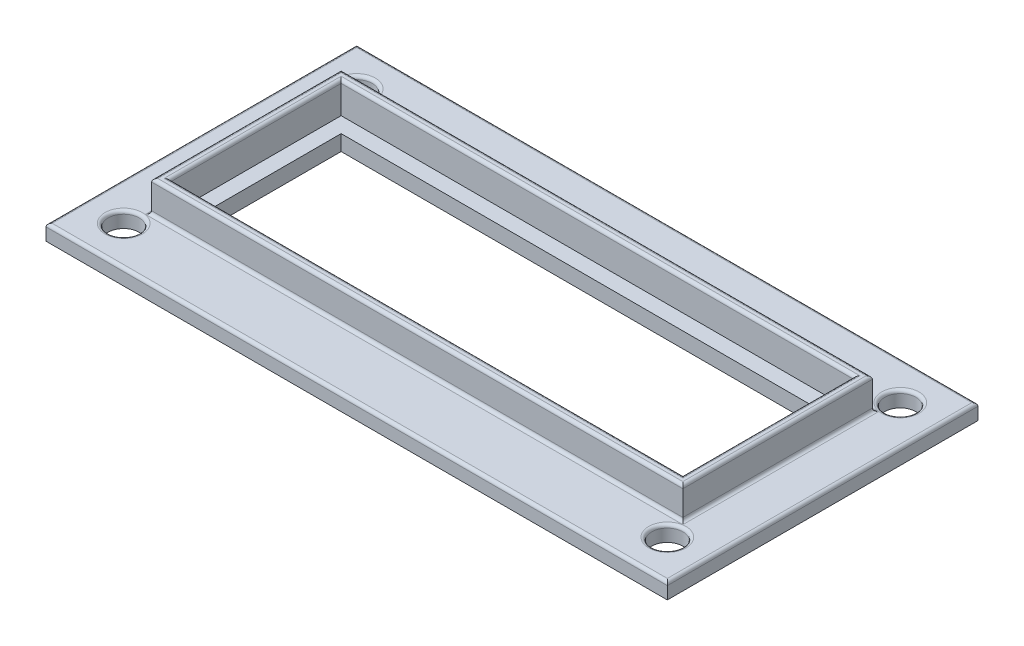
SolidWorks part; units mm, degrees
ref_plane "Front Plane" through (0, 0, 0) normal (0, 0, 1) x (1, 0, 0)
ref_plane "Top Plane" through (0, 0, 0) normal (0, 1, 0) x (1, 0, 0)
ref_plane "Right Plane" through (0, 0, 0) normal (1, 0, 0) x (0, 0, -1)
sketch "Sketch1" plane through (0, 0, 0) normal (0, 1, 0) x (1, 0, 0)
  line L0 (-85.5, 30.5) -> (-85.5, -30.5)
  line L1 (-82.5, 27.5) -> (82.5, 27.5)
  line L2 (-82.5, 27.5) -> (-82.5, -27.5)
  line L3 (-82.5, -27.5) -> (82.5, -27.5)
  line L4 (82.5, 27.5) -> (82.5, -27.5)
  line L5 (-82.5, 27.5) -> (82.5, -27.5) construction
  line L6 (-82.5, -27.5) -> (82.5, 27.5) construction
  line L7 (-85.5, -30.5) -> (85.5, -30.5)
  line L8 (85.5, 30.5) -> (85.5, -30.5)
  line L9 (-85.5, 30.5) -> (85.5, 30.5)
  point P0 (0, 0)
  dimension "D1" = 55
  dimension "D2" = 165
  dimension "D3" = 3
extrude "Boss-Extrude1" add sketch "Sketch1" along normal blind 10
sketch "Sketch2" plane through (0, 0, 0) normal (0, 1, 0) x (1, 0, 0)
  line L1 (-100, 50) -> (100, 50)
  line L2 (-100, 50) -> (-100, -50)
  line L3 (-100, -50) -> (100, -50)
  line L4 (100, 50) -> (100, -50)
  line L5 (-100, 50) -> (100, -50) construction
  line L6 (-100, -50) -> (100, 50) construction
  point P0 (0, 0)
  dimension "D1" = 200
  dimension "D2" = 100
extrude "Boss-Extrude2" add sketch "Sketch2" against normal blind 5
fillet "Fillet1" radius 1 8 edges at (0, 10, -27.5) (-82.5, 10, 0) (0, 10, 27.5) (82.5, 10, 0) (85.5, 10, 0) (0, 10, 30.5) (-85.5, 10, 0) (0, 10, -30.5)
sketch "Sketch3" plane through (0, 0, 0) normal (0, 1, 0) x (1, 0, 0)
  line L1 (-87.5, -37.5) -> (87.5, -37.5)
  line L2 (-87.5, -37.5) -> (-87.5, 37.5)
  line L3 (-87.5, 37.5) -> (87.5, 37.5)
  line L4 (87.5, -37.5) -> (87.5, 37.5)
  line L5 (-87.5, -37.5) -> (87.5, 37.5) construction
  line L6 (-87.5, 37.5) -> (87.5, -37.5) construction
  point P0 (0, 0)
  dimension "D1" = 175
  dimension "D2" = 75
hole_wizard "Ø10.0mm Dowel Hole1" positions "3DSketch1" profile "Sketch4" hole size "Ø10.0" standard "ISO" end condition through all
sketch3d "3DSketch1"
  point P0 (-87.5, 0, -37.5)
  point P3 (87.5, 0, -37.5)
  point P6 (87.5, 0, 37.5)
  point P9 (-87.5, 0, 37.5)
sketch "Sketch4" plane through (-87.5, 0, -37.5) normal (1, 0, 0) x (0, 0, 1)
  line L0 (0, 0) -> (0, 5)
  line L1 (0, 5) -> (5, 5)
  line L2 (5, 5) -> (5, 0)
  line L5 (5, 0) -> (0, 0)
  line L11 (0, -6.35) -> (0, 107.95) construction
  dimension "Thru Hole Dia." = 10
  dimension "Thru Hole Depth" = 5
fillet "Fillet2" radius 1 12 edges at (-85.5, 0, 0) (0, 0, 30.5) (85.5, 0, 0) (0, 0, -30.5) (0, 0, 50) (-100, 0, 0) (0, 0, -50) (100, 0, 0) (-87.5, 0, 42.5) (87.5, 0, 42.5) (87.5, 0, -32.5) (-87.5, 0, -32.5)
sketch "Sketch5" plane through (0, 0, 0) normal (0, 1, 0) x (1, 0, 0)
  line L0 (82.5, 27.5) -> (-82.5, 27.5) construction
  line L1 (-77.5, -22.5) -> (77.5, -22.5)
  line L2 (-77.5, -22.5) -> (-77.5, 22.5)
  line L3 (-77.5, 22.5) -> (77.5, 22.5)
  line L4 (77.5, -22.5) -> (77.5, 22.5)
  line L5 (-77.5, -22.5) -> (77.5, 22.5) construction
  line L6 (-77.5, 22.5) -> (77.5, -22.5) construction
  line L7 (82.5, -27.5) -> (82.5, 27.5) construction
  point P0 (0, 0)
  dimension "D1" = 5
  dimension "D2" = 5
extrude "Cut-Extrude2" cut sketch "Sketch5" along normal through all both and the other way through all
